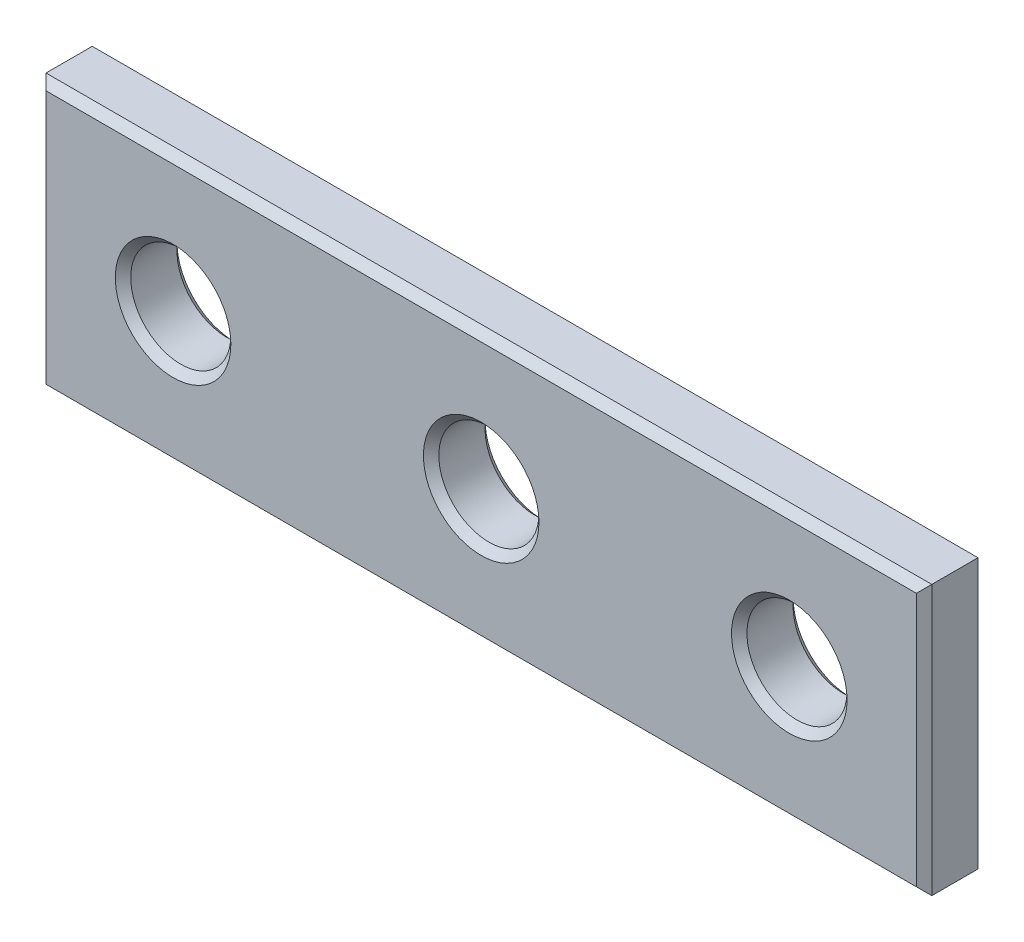
SolidWorks part; units mm, degrees
ref_plane "前视" through (0, 0, 0) normal (0, 0, 1) x (1, 0, 0)
ref_plane "上视" through (0, 0, 0) normal (0, 1, 0) x (1, 0, 0)
ref_plane "右视" through (0, 0, 0) normal (1, 0, 0) x (0, 0, -1)
sketch "草图1" plane through (0, 0, 0) normal (0, 0, 1) x (1, 0, 0)
  line L0 (87.3681, 0) -> (-80, 0) construction
  line L1 (-115, 35) -> (115, 35)
  line L2 (-115, 35) -> (-115, -35)
  line L3 (-115, -35) -> (115, -35)
  line L4 (115, 35) -> (115, -35)
  line L5 (0, 76.4471) -> (0, -77.2872) construction
  circle A0 centre (0, 0) radius 13
  circle A1 centre (80, 0) radius 13
  circle A2 centre (-80, 0) radius 13
  dimension "D5" = 80
  dimension "D1" = 70
  dimension "D2" = 230
  dimension "D3" = 35
  dimension "D4" = 115
  dimension "D6" = 80
extrude "基体-拉伸" add sketch "草图1" along normal blind 16
chamfer "倒角1" distance 2 angle 45 14 edges at (-67, 0, 0) (13, 0, 0) (0, -35, 0) (115, 0, 0) (0, 35, 0) (-115, 0, 0) (93, 0, 0) (-67, 0, 16) (13, 0, 16) (0, 35, 16) (115, 0, 16) (0, -35, 16) (-115, 0, 16) (93, 0, 16)
